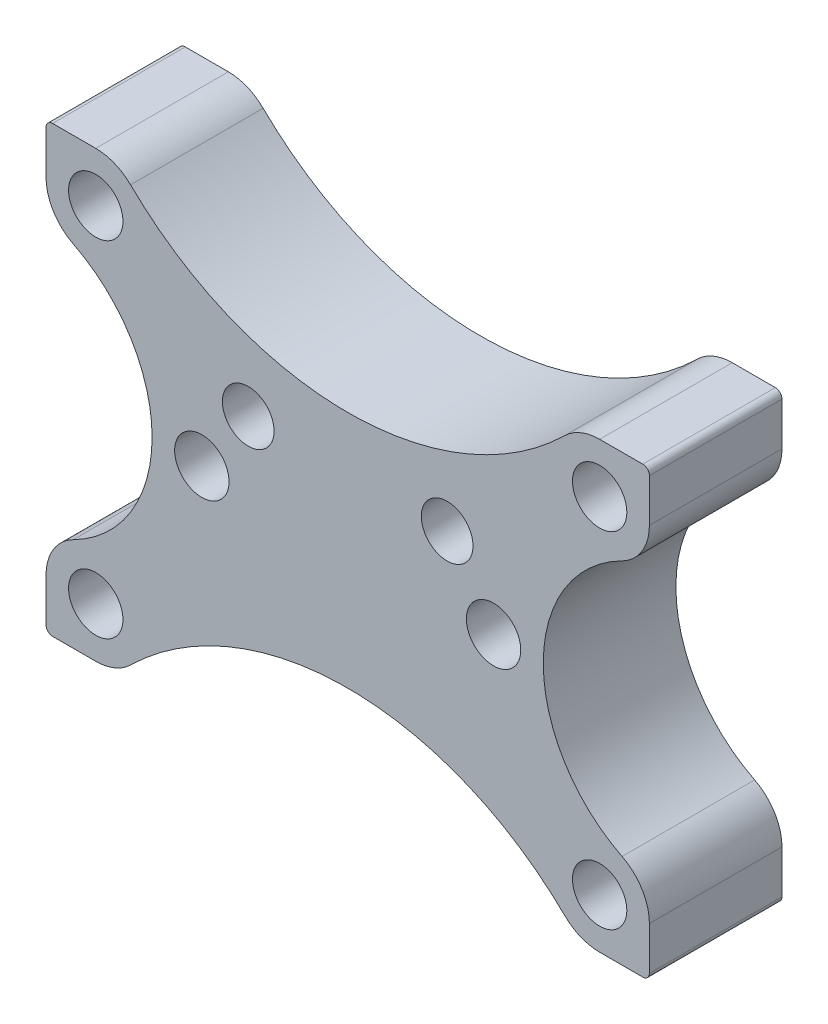
SolidWorks part; units mm, degrees
material "POM Acetal Copolymer"
ref_plane "Front Plane" through (0, 0, 0) normal (0, 0, 1) x (1, 0, 0)
ref_plane "Top Plane" through (0, 0, 0) normal (0, 1, 0) x (1, 0, 0)
ref_plane "Right Plane" through (0, 0, 0) normal (1, 0, 0) x (0, 0, -1)
sketch "Sketch1" plane through (0, 0, 0) normal (0, 0, 1) x (1, 0, 0)
  line L0 (-15, -995.7882) -> (-15, 49004.2118) construction
  line L1 (15, -1000.0301) -> (15, 48999.9699) construction
  line L2 (-13, -991.3231) -> (-13, 49008.6769) construction
  line L3 (-17, -994.4487) -> (-17, 49005.5513) construction
  line L4 (17, -1004.4057) -> (17, 48995.5943) construction
  line L5 (13, -1004.1825) -> (13, 48995.8175) construction
  line L6 (0, -1000) -> (0, 49000) construction
  line L7 (-1011.651, 0) -> (48988.349, 0) construction
  line L8 (-19, 13) -> (19, 13) construction
  line L9 (-19, -13) -> (19, -13) construction
  line L10 (-14.75, -10.691) -> (-14.75, -6.3917) construction
  line L11 (-7.5, 5) -> (7.5, 5) construction
  line L12 (-19, 13) -> (-19, -13) construction
  line L13 (19, 13) -> (19, -13) construction
  line L14 (14.75, -11.3222) -> (14.75, -4.7577) construction
  line L15 (7.5, 9) -> (-7.5, 9) construction
  line L17 (19, -15.05) -> (-19, -15.05) construction
  line L18 (-11, -2) -> (11, -2) construction
  line L19 (22.75, 16.75) -> (-22.75, 16.75) construction
  line L20 (19, -16.75) -> (-22.75, -16.75) construction
  line L21 (7.5, -9) -> (-7.5, -9) construction
  line L22 (-19, 16.75) -> (-22.75, 16.75)
  line L24 (-22.75, 16.75) -> (-22.75, 13)
  line L25 (-22.75, 16.75) -> (-22.75, -16.75) construction
  line L26 (22.75, 16.75) -> (22.75, -16.75) construction
  line L27 (-22.75, -13) -> (-22.75, -16.75)
  line L28 (-22.75, -16.75) -> (-19, -16.75)
  line L29 (19, -16.75) -> (22.75, -16.75)
  line L30 (22.75, -16.75) -> (22.75, -13)
  line L31 (19, 16.75) -> (22.75, 16.75)
  line L32 (22.75, 16.75) -> (22.75, 13)
  circle A0 centre (-19, 13) radius 2 construction
  circle A1 centre (-11, 0) radius 2 construction
  circle A3 centre (-19, -13) radius 2 construction
  circle A4 centre (11, 0) radius 2 construction
  circle A6 centre (19, 13) radius 2 construction
  circle A7 centre (19, -13) radius 2 construction
  arc A10 (-16.3772, 15.6802) -> (-19, 16.75) centre (-19, 13) ccw
  arc A11 (-16.3772, -15.6802) -> (-19, -16.75) centre (-19, -13) cw
  arc A12 (20.6899, -9.6524) -> (22.75, -13) centre (19, -13) cw
  arc A13 (20.6899, 9.6524) -> (22.75, 13) centre (19, 13) ccw
  arc A16 (20.6899, -9.6524) -> (20.6899, 9.6524) centre (25.5625, 0) cw
  arc A17 (-20.6899, 9.6524) -> (-20.6899, -9.6524) centre (-25.5625, 0) cw
  arc A18 (-16.3772, -15.6802) -> (16.3772, -15.6802) centre (0, -32.4153) cw
  arc A19 (16.3772, 15.6802) -> (-16.3772, 15.6802) centre (0, 32.4153) cw
  circle A20 centre (19, 13) radius 2.05
  circle A21 centre (-19, 13) radius 2.05
  circle A22 centre (-19, -13) radius 2.05
  circle A23 centre (19, -13) radius 2.05
  circle A24 centre (-11, 0) radius 2.05
  circle A25 centre (11, 0) radius 2.05
  circle A26 centre (7.5, 5) radius 1.95
  circle A27 centre (-7.5, 5) radius 1.95
  arc A28 (19, 16.75) -> (16.3772, 15.6802) centre (19, 13) ccw
  arc A29 (-22.75, 13) -> (-20.6899, 9.6524) centre (-19, 13) ccw
  arc A30 (-22.75, -13) -> (-20.6899, -9.6524) centre (-19, -13) cw
  arc A31 (19, -16.75) -> (16.3772, -15.6802) centre (19, -13) cw
  point P21 (0, 0)
  point P83 (13, 0)
  dimension "D4" = 4
  dimension "D6" = 5
  dimension "D12" = 1.75
  dimension "D13" = 15
  dimension "D15" = 4.1
  dimension "D18" = 1.75
  dimension "D11" = 3.9
  dimension "D8" = 26
  dimension "D1" = 30
  dimension "D2" = 4
  dimension "D3" = 4
  dimension "D5" = 3.75
  dimension "D7" = 45.5
  dimension "D9" = 14.75
  dimension "D10" = 9
extrude "Boss-Extrude1" add sketch "Sketch1" along normal blind 10
fillet "Fillet1" radius 0.5 4 edges at (-22.75, -16.75, 5) (-22.75, 16.75, 5) (22.75, 16.75, 5) (22.75, -16.75, 5)
